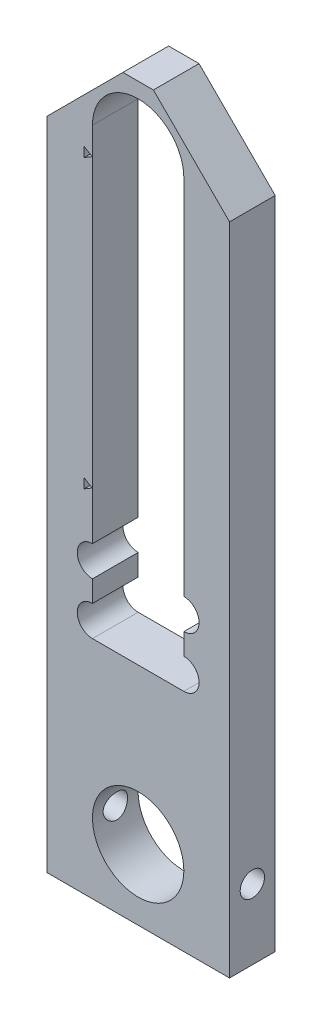
SolidWorks part; units mm, degrees
material "PW100:Mi:0:5:C1:0:1:2:Re:26:"
ref_plane "Plan1" through (0, 0, 0) normal (0, 0, 1) x (1, 0, 0)
ref_plane "Plan2" through (0, 0, 0) normal (0, 1, 0) x (1, 0, 0)
ref_plane "Plan3" through (0, 0, 0) normal (1, 0, 0) x (0, 0, -1)
sketch "Esquisse1" plane through (0, 0, 0) normal (0, 0, 1) x (1, 0, 0)
  line L0 (0, 215) -> (25, 240)
  line L1 (0, 0) -> (60, 0)
  line L2 (0, 0) -> (0, 215)
  line L3 (25, 240) -> (35, 240)
  line L4 (60, 0) -> (60, 215)
  line L5 (35, 240) -> (60, 215)
extrude "Base-Extrusion" add sketch "Esquisse1" along normal blind 15
sketch "Esquisse2" plane through (0, 0, 15) normal (0, 0, 1) x (1, 0, 0)
  circle A0 centre (30, 23) radius 15
extrude "Enlèv. mat.-Extru.1" cut sketch "Esquisse2" against normal blind 15
sketch "Esquisse3" plane through (0, 0, 15) normal (0, 0, 1) x (1, 0, 0)
  line L0 (45, 91) -> (45, 84)
  line L1 (15, 91) -> (15, 84)
  line L2 (15, 220) -> (15, 101)
  line L3 (15, 74) -> (45, 74)
  line L4 (45, 220) -> (45, 101)
  arc A0 (45, 220) -> (15, 220) centre (30, 220) ccw
  arc A1 (45, 74) -> (45, 84) centre (45, 79) ccw
  arc A2 (15, 84) -> (15, 74) centre (15, 79) ccw
  arc A3 (15, 101) -> (15, 91) centre (15, 96) ccw
  arc A4 (45, 91) -> (45, 101) centre (45, 96) ccw
extrude "Enlèv. mat.-Extru.2" cut sketch "Esquisse3" against normal blind 15
sketch "Esquisse4" plane through (0, 0, 0) normal (-1, 0, 0) x (0, 0, 1)
  circle A0 centre (7.5, 23) radius 4
extrude "Enlèv. mat.-Extru.3" cut sketch "Esquisse4" against normal through all
sketch "Esquisse5" plane through (0, 0, 15) normal (0, 0, 1) x (1, 0, 0)
  line L0 (15, 116.7779) -> (11.5997, 116.7779) construction
  line L1 (15, 220) -> (15, 101) construction
  line L2 (14.9022, 116.7779) -> (12.2393, 118.3779)
  line L3 (12.2393, 118.3779) -> (12.2393, 115.1779)
  line L4 (12.2393, 115.1779) -> (14.9022, 116.7779)
  dimension "D1" = 1.6
  dimension "D2" = 1.6
extrude "Enlèv. mat.-Extru.4" cut sketch "Esquisse5" against normal through all
pattern_linear "Répétition linéaire1" count 2 spacing 94.21
sketch "Esquisse6" plane through (0, 0, 15) normal (0, 0, 1) x (1, 0, 0)
  line L0 (15, 210.9994) -> (12.4109, 210.9994) construction
  line L1 (15, 220) -> (15, 101) construction
  dimension "D1" = 94.2214
